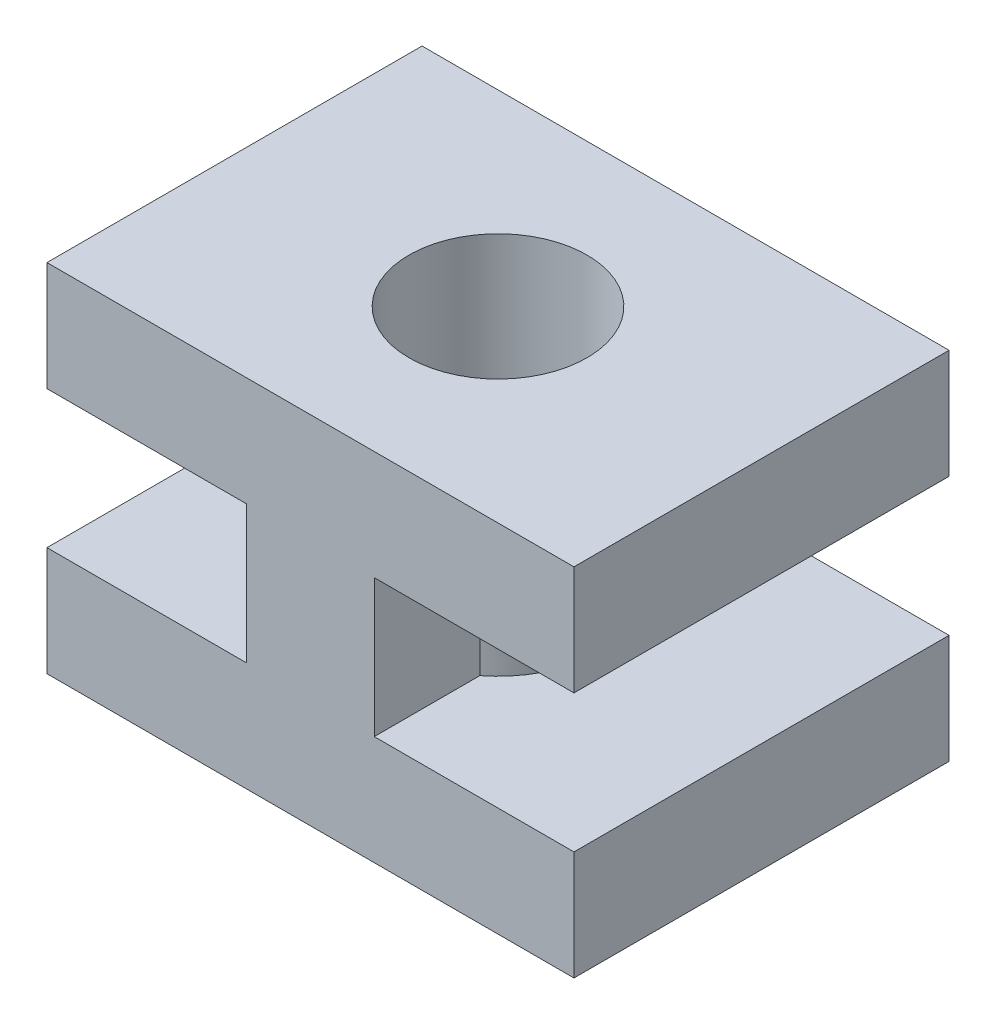
SolidWorks part; units mm, degrees
ref_plane "Front Plane" through (0, 0, 0) normal (0, 0, 1) x (1, 0, 0)
ref_plane "Top Plane" through (0, 0, 0) normal (0, 1, 0) x (1, 0, 0)
ref_plane "Right Plane" through (0, 0, 0) normal (1, 0, 0) x (0, 0, -1)
sketch "Sketch1" plane through (0, 0, 0) normal (0, 1, 0) x (1, 0, 0)
  line L0 (-1.075, -1.3809) -> (-1.075, -3.16)
  line L1 (-1.075, -3.16) -> (1.075, -3.16)
  line L2 (1.075, -3.16) -> (1.075, -1.3809)
  line L3 (0, 2.09) -> (0, -3.5147) construction
  circle A0 centre (0, 0) radius 1.5
  circle A1 centre (0, 0) radius 1.75
  point P12 (0, -3.16)
  dimension "D2" = 3.5
  dimension "D3" = 3
  dimension "D1" = 2.15
  dimension "D4" = 3.16
extrude "Boss-Extrude1" add sketch "Sketch1" along normal blind 1.16 contours L3 A1 L0 L1 | A1 L3 L1 L2 | L3 A1 A0 | A1 L3 A0
sketch "Sketch2" plane through (0, 1.16, 0) normal (0, 1, 0) x (1, 0, 0)
  line L0 (0, 4.05) -> (0, -5.7093) construction
  line L1 (-4.44, 3.16) -> (4.44, 3.16)
  line L2 (-4.44, 3.16) -> (-4.44, -3.16)
  line L3 (-4.44, -3.16) -> (4.44, -3.16)
  line L4 (4.44, 3.16) -> (4.44, -3.16)
  line L6 (-1.075, -3.16) -> (1.075, -3.16) construction
  circle A0 centre (0, 0) radius 1.5
  point P7 (0, -3.16)
  point P16 (0, -3.16)
  dimension "D2" = 3
  dimension "D1" = 6.32
  dimension "D3" = 3.16
  dimension "D4" = 8.88
extrude "Boss-Extrude2" add sketch "Sketch2" along normal blind 1.84
mirror "Mirror1" about plane through (0, 0, 0) normal (0, 1, 0) of "Boss-Extrude1", "Boss-Extrude2"
